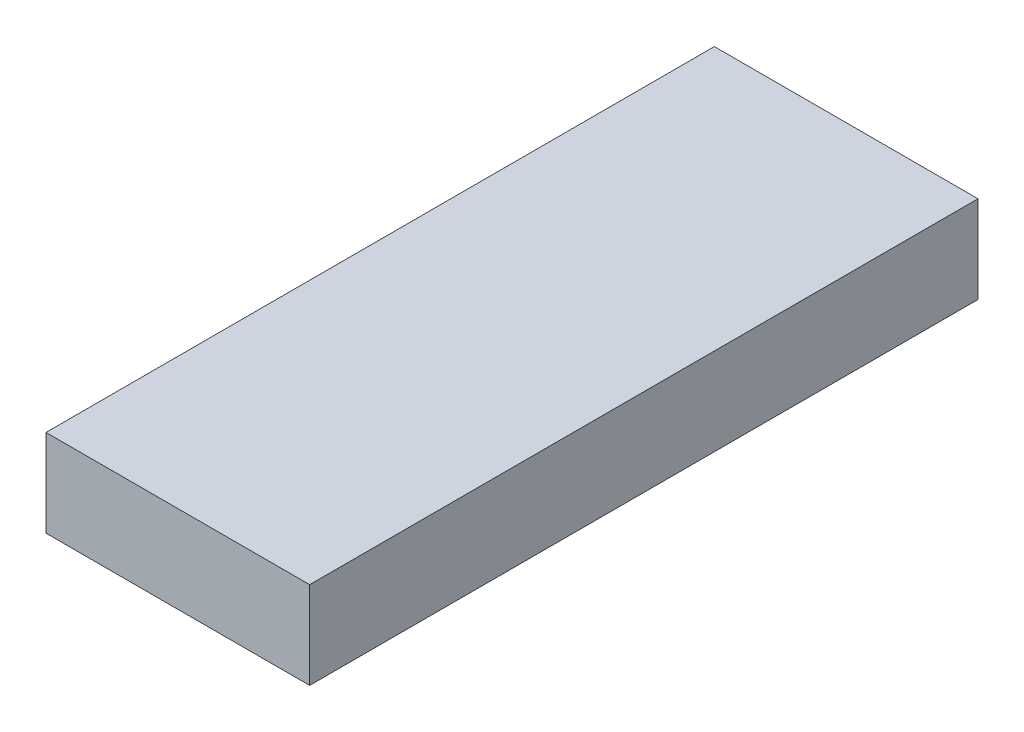
SolidWorks part; units mm, degrees
ref_plane "Front Plane" through (0, 0, 0) normal (0, 0, 1) x (1, 0, 0)
ref_plane "Top Plane" through (0, 0, 0) normal (0, 1, 0) x (1, 0, 0)
ref_plane "Right Plane" through (0, 0, 0) normal (1, 0, 0) x (0, 0, -1)
sketch "Sketch1" plane through (0, 0, 0) normal (0, 1, 0) x (1, 0, 0)
  line L1 (-9.017, 22.86) -> (9.017, 22.86)
  line L2 (-9.017, 22.86) -> (-9.017, -22.86)
  line L3 (-9.017, -22.86) -> (9.017, -22.86)
  line L4 (9.017, 22.86) -> (9.017, -22.86)
  line L5 (-9.017, 22.86) -> (9.017, -22.86) construction
  line L6 (-9.017, -22.86) -> (9.017, 22.86) construction
  point P0 (0, 0)
  dimension "D1" = 45.72
  dimension "D2" = 18.034
extrude "Boss-Extrude1" add sketch "Sketch1" along normal blind 5.969
